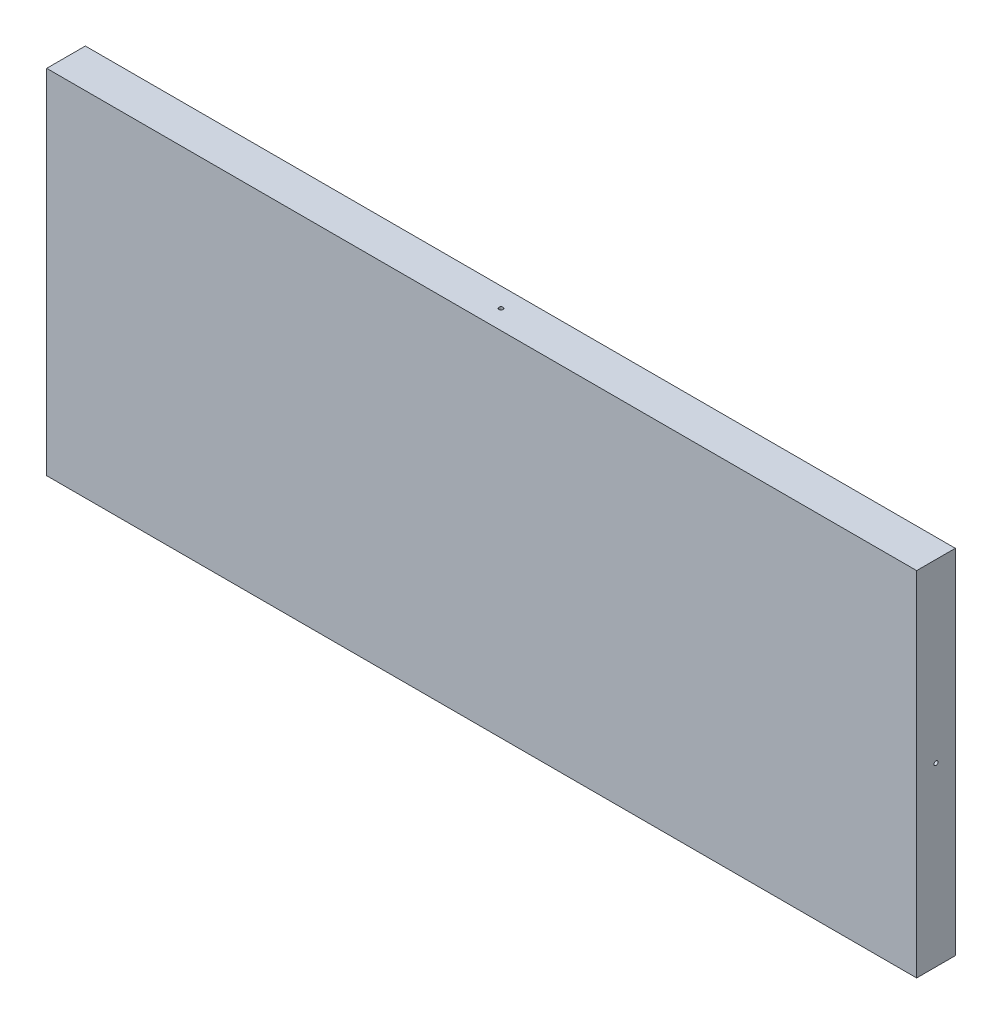
SolidWorks part; units mm, degrees
material "1.4511 (X3CrNb17)"
ref_plane "前视基准面" through (0, 0, 0) normal (0, 0, 1) x (1, 0, 0)
ref_plane "上视基准面" through (0, 0, 0) normal (0, 1, 0) x (1, 0, 0)
ref_plane "右视基准面" through (0, 0, 0) normal (1, 0, 0) x (0, 0, -1)
sketch "草图1" plane through (0, 0, 0) normal (0, 0, 1) x (1, 0, 0)
  line L1 (-450, 182.5) -> (450, 182.5)
  line L2 (-450, 182.5) -> (-450, -182.5)
  line L3 (-450, -182.5) -> (450, -182.5)
  line L4 (450, 182.5) -> (450, -182.5)
  line L5 (-450, 182.5) -> (450, -182.5) construction
  line L6 (-450, -182.5) -> (450, 182.5) construction
  point P0 (0, 0)
  dimension "D1" = 900
  dimension "D2" = 365
extrude "凸台-拉伸1" add sketch "草图1" along normal blind 40
sketch "草图2" plane through (0, 182.5, 0) normal (0, 1, 0) x (1, 0, 0)
  line L0 (-450, -40) -> (-450, 0) construction
  point P0 (0, -20)
  dimension "D1" = 450
hole_wizard "M5 螺纹孔1" positions "草图3" profile "草图4" tap size "M5" standard "GB" end condition through all
sketch "草图3" plane through (0, 182.5, 0) normal (0, 1, 0) x (1, 0, 0)
  point P0 (0, -20)
sketch "草图4" plane through (0, 182.5, 20) normal (1, 0, 0) x (0, 0, 1)
  line L0 (0, 0) -> (0, 365)
  line L1 (0, 365) -> (2.1, 365)
  line L2 (2.1, 365) -> (2.1, 0)
  line L5 (2.1, 0) -> (0, 0)
  line L11 (0, -6.35) -> (0, 107.95) construction
  dimension "通孔螺纹孔钻头直径" = 4.2
  dimension "通孔螺纹孔钻头深度" = 365
cosmetic thread "孔螺蚊线1"
sketch "草图5" plane through (-450, 0, 0) normal (-1, 0, 0) x (0, 0, 1)
  line L0 (40, 182.5) -> (0, 182.5) construction
  point P0 (20, 0)
  dimension "D1" = 182.5
hole_wizard "M5 螺纹孔2" positions "草图6" profile "草图7" tap size "M5" standard "GB" end condition through all
sketch "草图6" plane through (-450, 0, 0) normal (-1, 0, 0) x (0, 0, 1)
  point P0 (20, 0)
sketch "草图7" plane through (-450, 0, 20) normal (0, 1, 0) x (0, 0, 1)
  line L0 (0, 0) -> (0, 900)
  line L1 (0, 900) -> (2.1, 900)
  line L2 (2.1, 900) -> (2.1, 0)
  line L5 (2.1, 0) -> (0, 0)
  line L11 (0, -6.35) -> (0, 107.95) construction
  dimension "通孔螺纹孔钻头直径" = 4.2
  dimension "通孔螺纹孔钻头深度" = 900
cosmetic thread "孔螺蚊线2"
